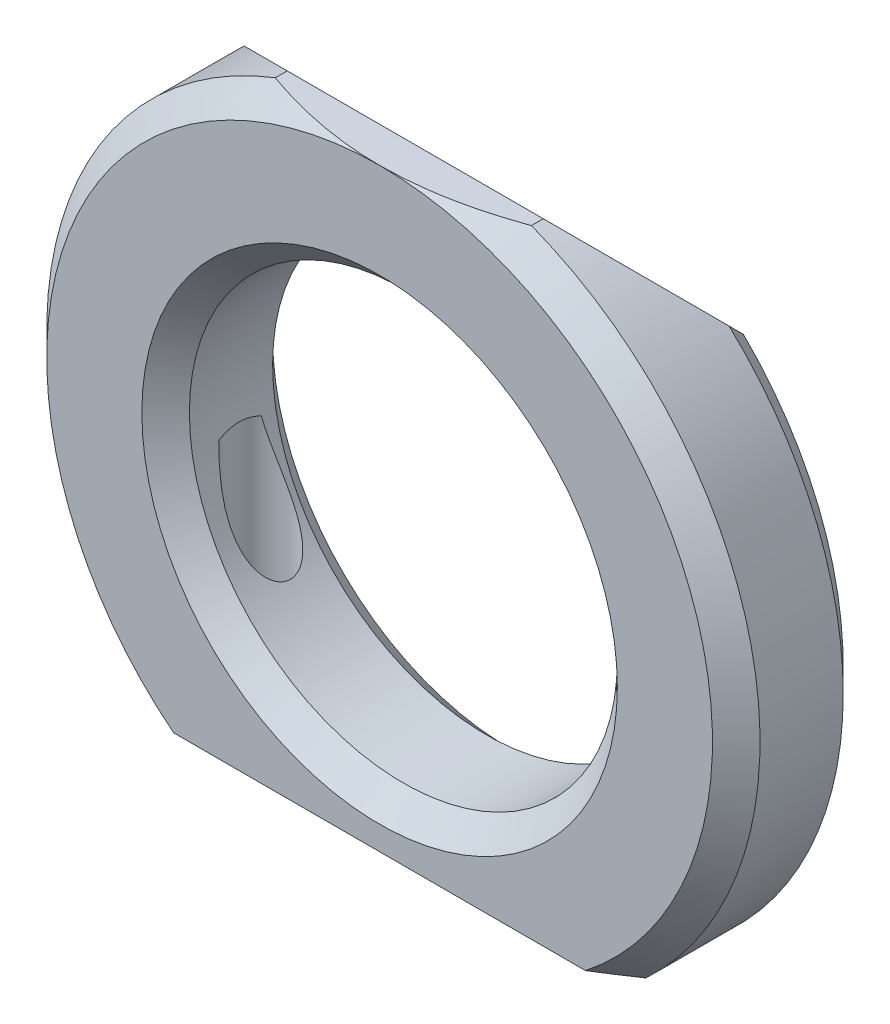
SolidWorks part; units mm, degrees
material "2A12"
ref_plane "前视基准面" through (0, 0, 0) normal (0, 0, 1) x (1, 0, 0)
ref_plane "上视基准面" through (0, 0, 0) normal (0, 1, 0) x (1, 0, 0)
ref_plane "右视基准面" through (0, 0, 0) normal (1, 0, 0) x (0, 0, -1)
sketch "草图1" plane through (0, 0, 0) normal (0, 0, 1) x (1, 0, 0)
  circle A0 centre (0, 0) radius 5.5
  circle A1 centre (0, 0) radius 7
  dimension "D1" = 11
  dimension "D2" = 14
extrude "拉伸1" add sketch "草图1" along normal mid plane 60
sketch "草图2" plane through (0, 0, 30) normal (0, 0, 1) x (1, 0, 0)
  line L0 (0, 0) -> (0, -11) construction
  line L1 (-10, 11) -> (10, 11) construction
  line L2 (-10, 11) -> (-10, -11) construction
  line L3 (-10, -11) -> (10, -11) construction
  line L4 (10, 11) -> (10, -11) construction
  circle A0 centre (0, 0) radius 5.5 construction
  circle A1 centre (0, 0) radius 5.5
  circle A2 centre (0, 0) radius 15
  dimension "D4" = 30
  dimension "D1" = 11
  dimension "D2" = 22
  dimension "D3" = 20
extrude "拉伸2" add sketch "草图2" against normal blind 7
mirror "镜向1" about plane through (0, 0, 0) normal (0, 0, 1) of "拉伸2"
sketch "草图4" plane through (0, 0, 30) normal (0, 0, 1) x (1, 0, 0)
  line L1 (-10.198, -11) -> (10.198, -11)
  line L2 (-10, -11) -> (10, -11) construction
  circle A0 centre (0, 0) radius 5.5 construction
  circle A1 centre (0, 0) radius 5.5
  circle A3 centre (0, 0) radius 15 construction
  arc A4 (10.198, -11) -> (-10.198, -11) centre (0, 0) ccw
extrude "拉伸3" [suppressed] add sketch "草图4" along normal blind 5
mirror "镜向2" [suppressed] about plane through (0, 0, 0) normal (0, 0, 1)
sketch "草图5" plane through (0, 0, 0) normal (1, 0, 0) x (0, 0, -1)
  line L0 (-30, 0) -> (30, 0) construction
  line L1 (-30, 15) -> (-30, -15) construction
  line L2 (30, -15) -> (30, 15) construction
  line L3 (-30, -11) -> (-24.5, -11)
  line L4 (-24.5, -11) -> (-24.5, -20)
  line L5 (24.5, -11) -> (24.5, -20)
  line L6 (-30, -11) -> (-30, -20)
  line L7 (-30, -20) -> (-24.5, -20)
  line L8 (30, -11) -> (30, -20)
  line L9 (30, -20) -> (24.5, -20)
  line L10 (24.5, -11) -> (30, -11)
  line L12 (-30, 15) -> (-30, -15) construction
  line L13 (30, -15) -> (30, 15) construction
  dimension "D1" = 9
  dimension "D2" = 11
  dimension "D4" = 5.5
  dimension "D5" = 5.5
extrude "拉伸4" cut sketch "草图5" against normal mid plane 30
sketch "草图6" plane through (0, -11, 0) normal (0, -1, 0) x (1, 0, 0)
  line L0 (0, 27.5) -> (0, -27.5) construction
  line L1 (-8, 27.5) -> (8, 27.5)
  line L2 (-8, 27.5) -> (-8, -27.5)
  line L3 (-8, -27.5) -> (8, -27.5)
  line L4 (8, 27.5) -> (8, -27.5)
  dimension "D1" = 16
  dimension "D2" = 55
hole_wizard "M3 螺纹孔1" positions "3D草图1" profile "草图7" tap size "M3" standard "GB"
sketch3d "3D草图1"
  point P0 (-8, -11, 27.5)
  point P3 (8, -11, 27.5)
  point P6 (-8, -11, -27.5)
  point P9 (8, -11, -27.5)
sketch "草图7" plane through (-8, -11, 27.5) normal (1, 0, 0) x (0, 0, -1)
  line L0 (0, 0) -> (0, 10.2511)
  line L1 (0, 10.2511) -> (1.25, 9.5)
  line L2 (1.25, 9.5) -> (1.25, 0)
  line L5 (1.25, 0) -> (0, 0)
  line L10 (0, 10.2511) -> (-1.25, 9.5) construction
  line L11 (0, -6.35) -> (0, 107.95) construction
  dimension "螺纹孔钻头直径" = 2.5
  dimension "螺纹孔钻头深度" = 9.5
  dimension "导头角度" = 118
cosmetic thread "孔螺蚊线1" parameters "D1"=8, "D2"=3
cosmetic thread "孔螺蚊线2" parameters "D1"=8, "D2"=3
cosmetic thread "孔螺蚊线3" parameters "D1"=8, "D2"=3
cosmetic thread "孔螺蚊线4" parameters "D1"=8, "D2"=3
chamfer "倒角1" [suppressed] distance 0.5 angle 45
chamfer "倒角2" [suppressed] distance 2 angle 45
chamfer "倒角3" [suppressed] distance 1 angle 45
fillet "圆角1" radius 1 2 edges at (-7, 0, -23) (7, 0, 23)
sketch "Sketch1" plane through (0, 0, 30) normal (0, 0, -1) x (-1, 0, 0)
  circle A0 centre (0, 0) radius 7.5
  dimension "D1" = 15
extrude "Extrude1" cut sketch "Sketch1" along normal blind 5
chamfer "Chamfer1" distance 1 angle 45 1 edges at (-5.5, 0, 25)
sketch "Sketch2" [suppressed] plane through (0, 0, -30) normal (0, 0, 1) x (1, 0, 0)
  line L0 (0, 0) -> (0, 11) construction
  line L1 (-12.5, 17) -> (12.5, 17)
  line L2 (-12.5, 17) -> (-12.5, 11)
  line L3 (-12.5, 11) -> (12.5, 11)
  line L4 (12.5, 17) -> (12.5, 11)
  dimension "D1" = 25
  dimension "D2" = 11
  dimension "D3" = 6
extrude "Extrude2" [suppressed] cut sketch "Sketch2" along normal up to surface (5.5 mm away)
sketch "Sketch4" [suppressed] plane through (0, 0, -24.5) normal (0, 0, -1) x (-1, 0, 0)
  circle A0 centre (0, 0) radius 17.5
  dimension "D1" = 35
extrude "Extrude4" [suppressed] cut sketch "Sketch4" against normal up to surface (54.5 mm away)
sketch "Sketch5" [suppressed] plane through (0, 0, -30) normal (0, 0, -1) x (-1, 0, 0)
  circle A0 centre (0, 0) radius 9
  dimension "D1" = 18
extrude "Extrude5" [suppressed] cut sketch "Sketch5" against normal blind 10
sketch "Sketch6" [suppressed] plane through (0, 0, -24.5) normal (0, 0, 1) x (1, 0, 0)
  circle A0 centre (0, 0) radius 15
extrude "Extrude6" [suppressed] cut sketch "Sketch6" against normal blind 0.5
chamfer "Chamfer3" [suppressed] distance 1 angle 45
sketch "草图8" [suppressed] plane through (0, 0, -30) normal (0, 0, -1) x (-1, 0, 0)
  line L3 (-10.198, -11) -> (10.198, -11)
  line L5 (-10.198, -11) -> (10.198, -11)
  circle A0 centre (0, 0) radius 9 construction
  circle A1 centre (0, 0) radius 9
  arc A2 (10.198, -11) -> (-10.198, -11) centre (0, 0) ccw
  arc A4 (10.198, -11) -> (-10.198, -11) centre (0, 0) ccw
  dimension "D1" = 0
extrude "拉伸5" [suppressed] add sketch "草图8" along normal blind 0.5
chamfer "倒角4" [suppressed] distance 1 angle 45
sketch "草图9" plane through (0, 0, -24.5) normal (0, 0, -1) x (-1, 0, 0)
  circle A0 centre (0, 0) radius 18
  dimension "D1" = 36
extrude "切除-拉伸1" cut sketch "草图9" against normal blind 55
sketch "草图10" plane through (0, 0, -30) normal (0, 0, -1) x (-1, 0, 0)
  circle A0 centre (0, 0) radius 9
  dimension "D1" = 18
extrude "切除-拉伸2" cut sketch "草图10" against normal through all
chamfer "倒角5" distance 1 angle 45 4 edges at (-9, 0, -24.5) (0, 15, -24.5) (0, 15, -30) (-9, 0, -30)
sketch "草图12" plane through (0, 0, 0) normal (1, 0, 0) x (0, 0, -1)
  line L0 (26, 14) -> (30, 10)
  line L1 (22, 14) -> (22, -11)
  line L2 (30, -10) -> (30, 10) construction
  line L4 (25.5, -11) -> (29, -11) construction
  line L5 (30, 10) -> (30, -11)
  line L6 (30, -11) -> (22, -11)
  line L7 (26, 14) -> (22, 14)
  point P2 (27.25, -11)
  dimension "D1" = 0
  dimension "D2" = 0
  dimension "D3" = 4
  dimension "D4" = 45
  dimension "D5" = 0
  dimension "D6" = 8
extrude "切除-拉伸4" cut sketch "草图12" against normal mid plane 30 flip side to cut
